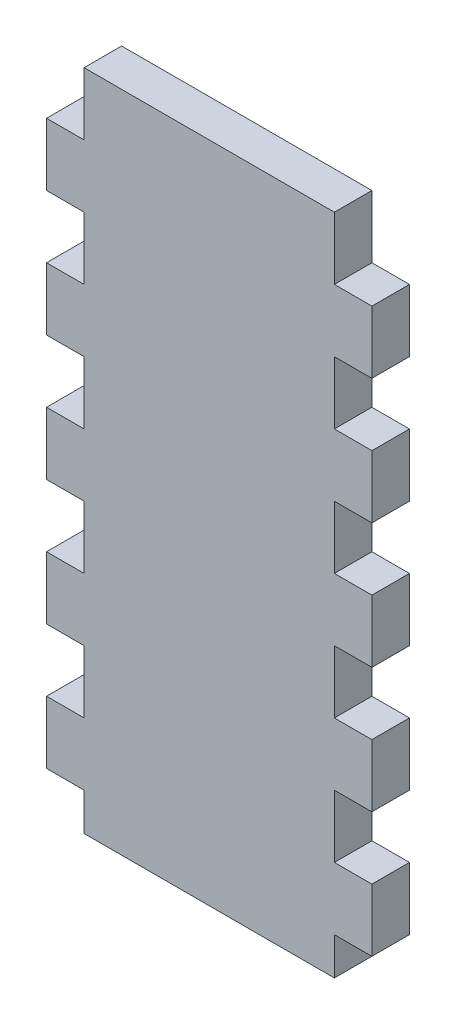
SolidWorks part; units mm, degrees
ref_plane "Plano frontal" through (0, 0, 0) normal (0, 0, 1) x (1, 0, 0)
ref_plane "Plano superior" through (0, 0, 0) normal (0, 1, 0) x (1, 0, 0)
ref_plane "Plano direito" through (0, 0, 0) normal (1, 0, 0) x (0, 0, -1)
sketch "Esboço2" plane through (0, 0, 0) normal (0, 0, 1) x (1, 0, 0)
  line L0 (-5.6107, 21.5167) -> (-5.6107, 16.5167)
  line L1 (-5.6107, 21.5167) -> (14.3893, 21.5167)
  line L5 (-5.6107, 16.5167) -> (-8.6107, 16.5167)
  line L6 (-8.6107, 16.5167) -> (-8.6107, 11.5167)
  line L7 (-8.6107, 11.5167) -> (-5.6107, 11.5167)
  line L8 (-5.6107, 11.5167) -> (-5.6107, 6.5167)
  line L9 (-5.6107, 6.5167) -> (-8.6107, 6.5167)
  line L10 (-8.6107, 6.5167) -> (-8.6107, 1.5167)
  line L11 (-8.6107, 1.5167) -> (-5.6107, 1.5167)
  line L12 (-5.6107, 1.5167) -> (-5.6107, -3.4833)
  line L13 (-5.6107, -3.4833) -> (-8.6107, -3.4833)
  line L14 (-8.6107, -3.4833) -> (-8.6107, -8.4833)
  line L15 (-8.6107, -8.4833) -> (-5.6107, -8.4833)
  line L16 (-5.6107, -8.4833) -> (-5.6107, -13.4833)
  line L17 (-5.6107, -13.4833) -> (-8.6107, -13.4833)
  line L18 (-8.6107, -13.4833) -> (-8.6107, -18.4833)
  line L19 (-8.6107, -18.4833) -> (-5.6107, -18.4833)
  line L20 (-5.6107, -18.4833) -> (-5.6107, -23.4833)
  line L21 (-5.6107, -23.4833) -> (-8.6107, -23.4833)
  line L22 (-8.6107, -23.4833) -> (-8.6107, -28.4833)
  line L23 (-8.6107, -28.4833) -> (-5.6107, -28.4833)
  line L24 (-5.6107, -28.4833) -> (-5.6107, -31.4833)
  line L25 (17.3893, -28.4833) -> (14.3893, -28.4833)
  line L26 (17.3894, -23.4854) -> (17.3893, -28.4833)
  line L27 (14.3894, -23.4854) -> (17.3894, -23.4854)
  line L28 (14.3894, -18.4854) -> (14.3894, -23.4854)
  line L29 (17.3894, -18.4854) -> (14.3894, -18.4854)
  line L30 (17.3894, -13.4854) -> (17.3894, -18.4854)
  line L31 (14.3894, -13.4854) -> (17.3894, -13.4854)
  line L32 (14.3894, -8.4854) -> (14.3894, -13.4854)
  line L33 (17.3894, -8.4854) -> (14.3894, -8.4854)
  line L34 (17.3894, -3.4854) -> (17.3894, -8.4854)
  line L35 (14.3894, -3.4854) -> (17.3894, -3.4854)
  line L36 (14.3894, 1.5146) -> (14.3894, -3.4854)
  line L37 (17.3917, 1.5146) -> (14.3894, 1.5146)
  line L38 (17.3917, 6.5146) -> (17.3917, 1.5146)
  line L39 (14.3893, 6.5146) -> (17.3917, 6.5146)
  line L40 (14.3893, 11.5167) -> (14.3893, 6.5146)
  line L41 (17.3893, 11.5167) -> (14.3893, 11.5167)
  line L42 (17.3893, 16.5167) -> (17.3893, 11.5167)
  line L44 (14.3893, 21.5167) -> (14.3893, 16.5167)
  line L45 (-5.6107, -31.4833) -> (14.3893, -31.4833)
  line L46 (14.3893, -31.4833) -> (14.3893, -28.4833)
  line L47 (14.3893, 16.5167) -> (17.3893, 16.5167)
  point P9 (17.3906, 16.5147)
  point P19 (17.3906, 11.5146)
  point P24 (17.3906, -8.4854)
  point P28 (14.3906, -3.4854)
  point P48 (17.3916, 1.5146)
  point P49 (14.3893, 6.5146)
  point P50 (14.4119, 11.5146)
  dimension "D1" = 5
  dimension "D2" = 20
  dimension "D3" = 3
  dimension "D4" = 3
  dimension "D5" = 20
  dimension "D7" = 5
  dimension "D8" = 5
  dimension "D10" = 3
  dimension "D11" = 3
  dimension "D13" = 3
  dimension "D14" = 5
  dimension "D15" = 3
  dimension "D16" = 5
  dimension "D17" = 3
  dimension "D18" = 5
  dimension "D19" = 3
  dimension "D20" = 5
  dimension "D21" = 5
  dimension "D22" = 5
  dimension "D23" = 5.0021
  dimension "D24" = 3
  dimension "D25" = 3.0024
  dimension "D26" = 3.0023
  dimension "D27" = 3
  dimension "D6" = 5
extrude "Ressalto-extrusão2" add sketch "Esboço2" along normal blind 3
